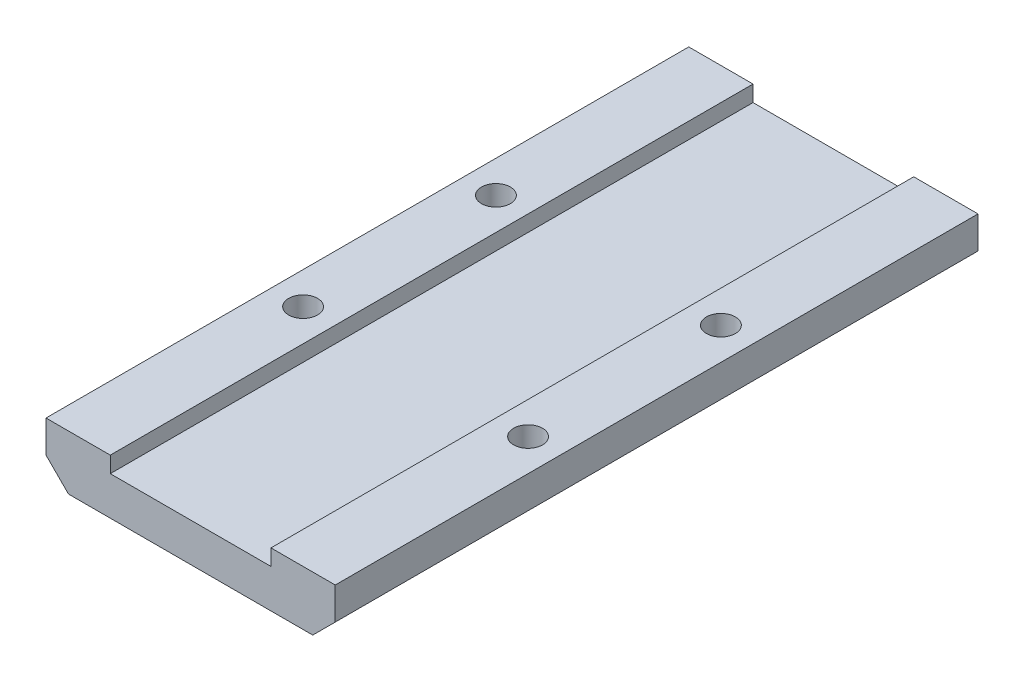
SolidWorks part; units mm, degrees
ref_plane "前视基准面" through (0, 0, 0) normal (0, 0, 1) x (1, 0, 0)
ref_plane "上视基准面" through (0, 0, 0) normal (0, 1, 0) x (1, 0, 0)
ref_plane "右视基准面" through (0, 0, 0) normal (1, 0, 0) x (0, 0, -1)
sketch "草图1" plane through (0, 0, 0) normal (0, 0, 1) x (1, 0, 0)
  line L0 (38, 0) -> (-38, 0)
  line L1 (-38, 0) -> (-45, 7)
  line L2 (-45, 7) -> (-45, 17)
  line L3 (-45, 17) -> (-25, 17)
  line L4 (-25, 17) -> (-25, 12)
  line L5 (-25, 12) -> (25, 12)
  line L6 (0, 12) -> (0, 0) construction
  line L7 (25, 17) -> (25, 12)
  line L8 (38, 0) -> (45, 7)
  line L9 (45, 7) -> (45, 17)
  line L10 (45, 17) -> (25, 17)
  dimension "D1" = 90
  dimension "D2" = 17
  dimension "D3" = 5
  dimension "D4" = 7
  dimension "D5" = 7
  dimension "D6" = 50
extrude "凸台-拉伸1" add sketch "草图1" along normal blind 200
sketch "草图2" plane through (0, 17, 0) normal (0, 1, 0) x (1, 0, 0)
  line L0 (-25, -200) -> (-45, -200) construction
  line L1 (0, 0) -> (0, -43.109) construction
  circle A0 centre (-35, -130) radius 4.5
  dimension "D1" = 9
  dimension "D2" = 70
  dimension "D3" = 70
extrude "切除-拉伸1" cut sketch "草图2" against normal up to next
pattern_linear "阵列(线性)1" count 2 spacing 60 along (0, 0, -1) count 2 spacing 70 along (1, 0, 0) of "切除-拉伸1"
